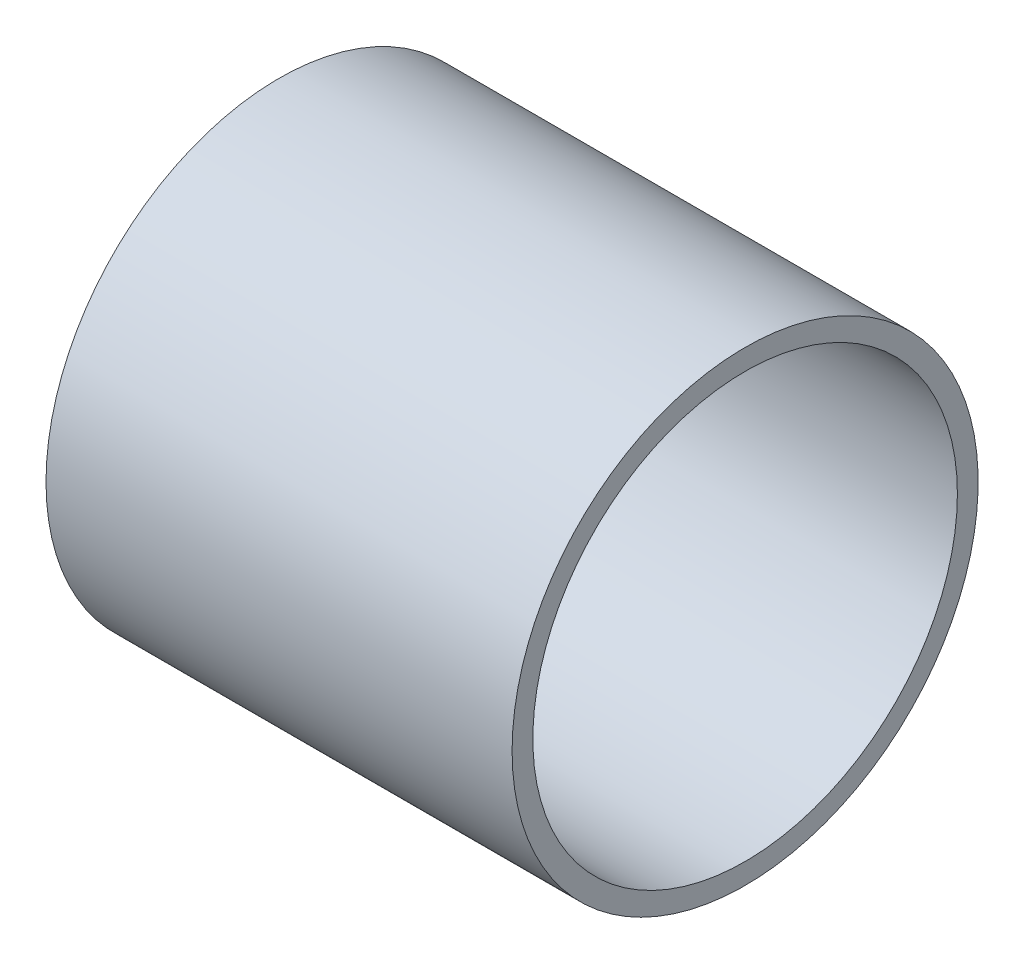
SolidWorks part; units mm, degrees
ref_plane "Front Plane" through (0, 0, 0) normal (0, 0, 1) x (1, 0, 0)
ref_plane "Top Plane" through (0, 0, 0) normal (0, 1, 0) x (1, 0, 0)
ref_plane "Right Plane" through (0, 0, 0) normal (1, 0, 0) x (0, 0, -1)
sketch "Sketch1" plane through (0, 0, 0) normal (0, 0, 1) x (1, 0, 0)
  line L1 (-5.5, 2.75) -> (5.5, 2.75)
  line L2 (-5.5, 2.75) -> (-5.5, -2.75)
  line L3 (-5.5, -2.75) -> (5.5, -2.75)
  line L4 (5.5, 2.75) -> (5.5, -2.75)
  line L5 (-5.5, 2.75) -> (5.5, -2.75) construction
  line L6 (-5.5, -2.75) -> (5.5, 2.75) construction
  point P0 (0, 0)
  dimension "D1" = 11
  dimension "D2" = 5.5
revolve "Revolve1" add sketch "Sketch1" angle 360 about L3
sketch "Sketch3" plane through (5.5, 0, 0) normal (1, 0, 0) x (0, 0, -1)
  line L0 (-5.5, -2.75) -> (5.5, -2.75) construction
  circle A0 centre (0, -2.75) radius 5.5 construction
  circle A1 centre (0, -2.75) radius 5.01
  dimension "D1" = 10.02
extrude "Cut-Extrude1" cut sketch "Sketch3" against normal through all
